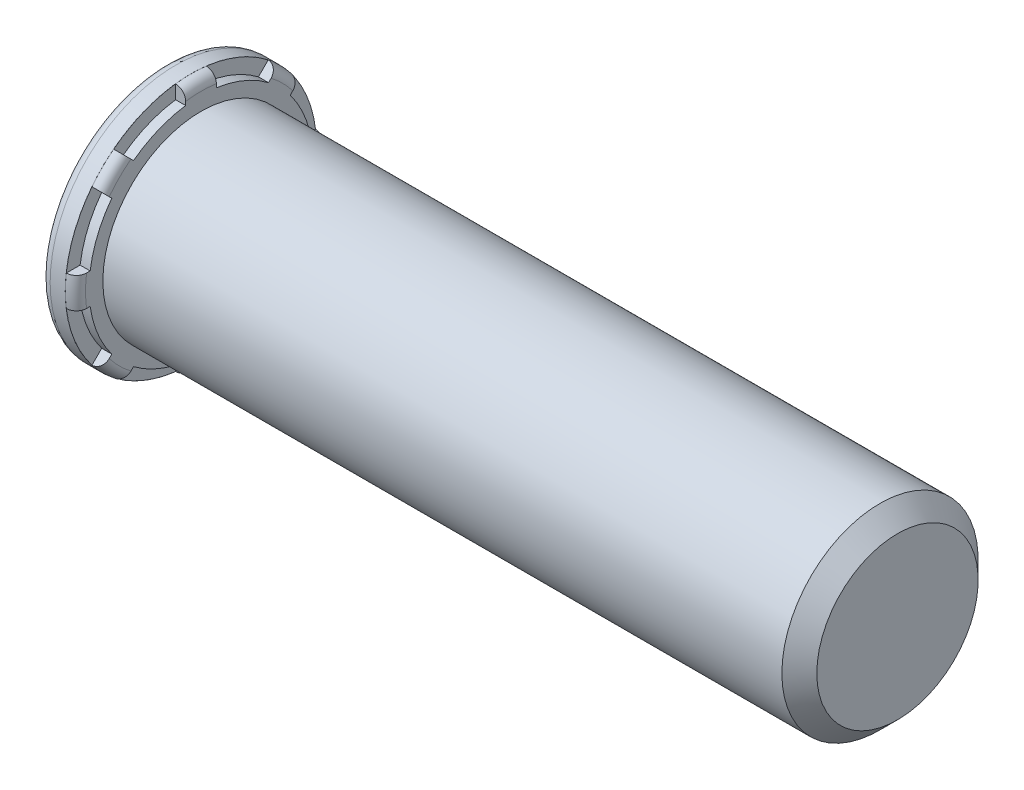
SolidWorks part; units mm, degrees
revolve "BaseBody" add sketch "BodySke" angle 360 about L6
sketch "BodySke" plane through (0, 0, 0) normal (0, 0, 1) x (1, 0, 0)
  line L0 (-0.64, 2.944) -> (-0.64, 0)
  line L1 (0.2585, 2.9415) -> (0.2585, 2.5)
  line L3 (0.2585, 2.5) -> (17.555, 2.5)
  line L4 (18, 2.055) -> (18, 0)
  line L5 (18, 0) -> (-0.64, 0)
  line L6 (0, 0) -> (50.554, 0) construction
  line L8 (18, 2.055) -> (17.555, 2.5)
  line L9 (-0.384, 3.2) -> (0, 3.2)
  line L10 (0.0025, 3.1975) -> (0, 3.1975)
  line L11 (0.8, 19.05) -> (0.8, -3.175) construction
  line L12 (0, 3.1975) -> (0, 3.2)
  arc A0 (-0.64, 2.944) -> (-0.384, 3.2) centre (-0.384, 2.944) cw
  arc A1 (0.0025, 3.1975) -> (0.2585, 2.9415) centre (0.0025, 2.9415) cw
  dimension "Fillet_rad" = 0.256
  dimension "Body_ch_ang" = 45
  dimension "Minor_dia" = 4.11
  dimension "Diameter" = 5
  dimension "T_dim" = 0.64
  dimension "H_dia" = 6.4
  dimension "D2" = 0.0025
  dimension "D3" = 0.0025
  dimension "Length" = 18
  dimension "Advance" = 0.8
cosmetic thread "ThreadCosmetic" [suppressed] parameters "Thread_length"=15.7, "Thread_minor"=4.11
ref_plane "Plane1" through (0, 0, 0) normal (0, 0, 1) x (1, 0, 0)
ref_plane "Plane2" through (0, 0, 0) normal (0, 1, 0) x (1, 0, 0)
ref_plane "Plane3" through (0, 0, 0) normal (1, 0, 0) x (0, 0, -1)
sketch "ThdSchSke" plane through (0, 0, 0) normal (0, 0, 1) x (1, 0, 0)
  line L0 (2.3, -2.055) -> (1.9884, -2.5)
  line L1 (2.3, -2.055) -> (2.6116, -2.5)
  line L2 (2.6116, -2.5) -> (2.6116, -3.125)
  line L3 (-3.175, 0) -> (5.1513, 0) construction
  line L4 (0, -3.2) -> (0, 3.2) construction
  line L5 (2.6116, -3.125) -> (1.9884, -3.125)
  line L6 (1.9884, -3.125) -> (1.9884, -2.5)
  dimension "Diameter" = 5
  dimension "Thread_minor" = 4.11
  dimension "Start" = 2.3
revolve "ThreadSchematic" [suppressed] cut sketch "ThdSchSke" angle 360 about L3
pattern_linear "ThdSchPat" [suppressed]
sketch "RibCutSke" plane through (0.2585, 1.7944, -0.091) normal (1, 0, 0) x (0, 0, -1)
  line L0 (0.3001, 1.0286) -> (0.3001, 1.3816)
  line L1 (1.6287, 0.4783) -> (1.8783, 0.7279)
  line L2 (0.3001, 0.6748) -> (0.3001, 2.4006) construction
  line L3 (-0.091, -1.7944) -> (-0.091, 5.0239) construction
  line L4 (-0.091, -1.7944) -> (0.3001, 0.6748) construction
  line L5 (-0.091, -1.7944) -> (1.3785, 0.2281) construction
  line L6 (1.3785, 0.2281) -> (2.6039, 1.4535) construction
  circle A0 centre (-0.091, -1.7944) radius 2.9415 construction
  arc A1 (1.6287, 0.4783) -> (0.3001, 1.0286) centre (-0.091, -1.7944) ccw
  arc A2 (1.8783, 0.7279) -> (0.3001, 1.3816) centre (-0.091, -1.7944) ccw
  circle A4 centre (-0.091, -1.7944) radius 2.5 construction
  dimension "Rib_root_half_angle" = 9
  dimension "Rib_root_gap_angle" = 27
  dimension "Angle" = 45
extrude "RibCut" cut sketch "RibCutSke" against normal blind 0.2561
pattern_circular "RibCutsPat" count 8 every 45 about axis through (0, 0, 0) along (1, 0, 0) of "RibCut"
equation "' \"Length@BodySke\" = 18"
equation "' \"H_dia@BodySke\" = 6.4"
equation "' \"Start@ThdSchSke\" = 2.3"
equation "' \"T_dim@BodySke\" = 0.64"
equation "' \"Diameter@BodySke\" = 5"
equation "' \"Minor_dia@BodySke\" = 4.11"
equation "' \"Advance@BodySke\" = 0.8"
equation "\"Fillet_rad@BodySke\" =  \"T_dim@BodySke\" * 0.4"
equation "\"Num_ribs@RibCutsPat\" = 8"
equation "\"Angle@RibCutSke\" =\"Angle@RibCutsPat\""
equation "\"Rib_root_half_angle@RibCutSke\" = \"Angle@RibCutSke\" / 5"
equation "\"Rib_root_gap_angle@RibCutSke\" = \"Angle@RibCutSke\" - (2 * \"Rib_root_half_angle@RibCutSke\" )"
equation "\"Rib_root_dia@RibCutSke\" = \"Diameter@BodySke\""
equation "\"Inner_dia@RibCutSke\" = ( \"H_dia@BodySke\" + \"Diameter@BodySke\" ) / 2"
equation "\"Outer_dia@RibCutSke\" = \"H_dia@BodySke\""
equation "\"Depth@RibCut\" =  \"Fillet_rad@BodySke\" + 0.0001"
equation "\"Thread_length@ThreadCosmetic\" = \"Length@BodySke\" - \"Start@ThdSchSke\""
equation "\"Thread_minor@ThreadCosmetic\" = \"Minor_dia@BodySke\""
equation "\"Thread_minor@ThdSchSke\" = \"Minor_dia@BodySke\""
equation "\"Diameter@ThdSchSke\" = \"Diameter@BodySke\""
equation "\"Overcut@ThdSchSke\" = \"Diameter@BodySke\" * 1.25"
equation "\"Num_threads@ThdSchPat\" = int( \"Thread_length@ThreadCosmetic\" / \"Advance@BodySke\" + 0.999 )  + 1"
equation "\"Advance@ThdSchPat\" = \"Thread_length@ThreadCosmetic\" /  (\"Num_threads@ThdSchPat\" - 1) 'relax it"
equation "\"Num_threads@ThdSchPat\" = \"Num_threads@ThdSchPat\" - sgn( \"Num_threads@ThdSchPat\" - 1) '---chamfered tips only---"
